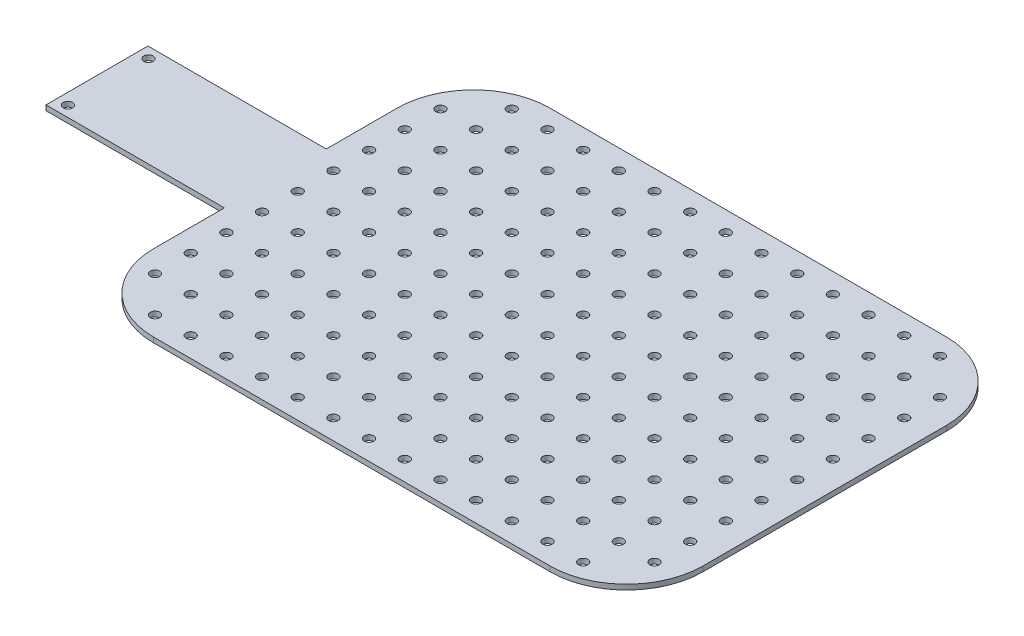
SolidWorks part; units mm, degrees
ref_plane "Front Plane" through (0, 0, 0) normal (0, 0, 1) x (1, 0, 0)
ref_plane "Top Plane" through (0, 0, 0) normal (0, 1, 0) x (1, 0, 0)
ref_plane "Right Plane" through (0, 0, 0) normal (1, 0, 0) x (0, 0, -1)
sketch "Sketch1" plane through (0, 0, 0) normal (0, 1, 0) x (1, 0, 0)
  line L0 (0, 0) -> (0, 155.575) construction
  line L1 (77.8, 155.575) -> (-77.8, 155.575)
  line L2 (-107.8, 125.575) -> (-107.8, 97.7875)
  line L3 (-107.8, 97.7875) -> (-177.8, 97.7875)
  line L4 (-177.8, 97.7875) -> (-177.8, 57.7875)
  line L5 (-177.8, 57.7875) -> (-107.8, 57.7875)
  line L6 (-107.8, 57.7875) -> (-107.8, 30)
  line L7 (-77.8, 0) -> (77.8, 0)
  line L8 (-173.4, 93.5875) -> (-173.4, 61.9875) construction
  line L9 (-177.8, 77.7875) -> (-107.8, 77.7875) construction
  line L10 (107.8, 97.7875) -> (107.8, 57.7875)
  line L11 (107.8, 57.7875) -> (107.8, 30)
  line L15 (107.8, 125.575) -> (107.8, 97.7875)
  circle A0 centre (-173.4, 93.5875) radius 1.85
  circle A1 centre (-173.4, 61.9875) radius 1.85
  arc A4 (107.8, 30) -> (77.8, 0) centre (77.8, 30) cw
  arc A5 (-107.8, 30) -> (-77.8, 0) centre (-77.8, 30) ccw
  arc A6 (107.8, 125.575) -> (77.8, 155.575) centre (77.8, 125.575) ccw
  arc A7 (-77.8, 155.575) -> (-107.8, 125.575) centre (-77.8, 125.575) ccw
  point P15 (-173.4, 77.7875)
  point P29 (107.8, 0)
  point P32 (-107.8, 0)
  point P35 (107.8, 155.575)
  point P38 (-107.8, 155.575)
  dimension "D5" = 3.7
  dimension "D8" = 30
  dimension "D1" = 155.575
  dimension "D2" = 177.8
  dimension "D3" = 40
  dimension "D4" = 31.6
  dimension "D6" = 4.4
  dimension "D7" = 70
extrude "Boss-Extrude1" add sketch "Sketch1" along normal blind 2
sketch "Sketch2" plane through (0, 2, 0) normal (0, 1, 0) x (1, 0, 0)
  line L0 (-99.0132, 8.7868) -> (-99.0132, 146.7882) construction
  line L1 (-99.0132, 146.7882) -> (99.0132, 146.7882) construction
  line L2 (99.0132, 146.7882) -> (99.0132, 8.7868) construction
  line L3 (99.0132, 8.7868) -> (-99.0132, 8.7868) construction
  line L4 (-177.8, 77.7875) -> (107.8, 77.7875) construction
  line L5 (-177.8, 97.7875) -> (-177.8, 57.7875) construction
  line L7 (107.8, 30) -> (107.8, 125.575) construction
  arc A0 (-107.8, 30) -> (-77.8, 0) centre (-77.8, 30) ccw construction
  arc A1 (-77.8, 155.575) -> (-107.8, 125.575) centre (-77.8, 125.575) ccw construction
  arc A2 (107.8, 125.575) -> (77.8, 155.575) centre (77.8, 125.575) ccw construction
  arc A3 (77.8, 0) -> (107.8, 30) centre (77.8, 30) ccw construction
  circle A4 centre (-99.0132, 21.7875) radius 1.85
  circle A5 centre (-99.0132, 35.7875) radius 1.85
  circle A6 centre (-99.0132, 49.7875) radius 1.85
  circle A7 centre (-99.0132, 63.7875) radius 1.85
  circle A8 centre (-99.0132, 77.7875) radius 1.85
  circle A9 centre (-99.0132, 91.7875) radius 1.85
  circle A10 centre (-99.0132, 105.7875) radius 1.85
  circle A11 centre (-99.0132, 119.7875) radius 1.85
  circle A12 centre (-99.0132, 133.7875) radius 1.85
  circle A13 centre (-85.0132, 63.7875) radius 1.85
  circle A14 centre (-85.0132, 49.7875) radius 1.85
  circle A15 centre (-85.0132, 35.7875) radius 1.85
  circle A16 centre (-85.0132, 21.7875) radius 1.85
  circle A17 centre (-85.0132, 91.7875) radius 1.85
  circle A18 centre (-85.0132, 105.7875) radius 1.85
  circle A19 centre (-85.0132, 77.7875) radius 1.85
  circle A20 centre (-85.0132, 133.7875) radius 1.85
  circle A21 centre (-85.0132, 119.7875) radius 1.85
  circle A22 centre (-71.0132, 63.7875) radius 1.85
  circle A23 centre (-71.0132, 49.7875) radius 1.85
  circle A24 centre (-71.0132, 35.7875) radius 1.85
  circle A25 centre (-71.0132, 21.7875) radius 1.85
  circle A26 centre (-71.0132, 91.7875) radius 1.85
  circle A27 centre (-71.0132, 105.7875) radius 1.85
  circle A28 centre (-71.0132, 77.7875) radius 1.85
  circle A29 centre (-71.0132, 133.7875) radius 1.85
  circle A30 centre (-71.0132, 119.7875) radius 1.85
  circle A31 centre (-57.0132, 63.7875) radius 1.85
  circle A32 centre (-57.0132, 49.7875) radius 1.85
  circle A33 centre (-57.0132, 35.7875) radius 1.85
  circle A34 centre (-57.0132, 21.7875) radius 1.85
  circle A35 centre (-57.0132, 91.7875) radius 1.85
  circle A36 centre (-57.0132, 105.7875) radius 1.85
  circle A37 centre (-57.0132, 77.7875) radius 1.85
  circle A38 centre (-57.0132, 133.7875) radius 1.85
  circle A39 centre (-57.0132, 119.7875) radius 1.85
  circle A40 centre (-43.0132, 63.7875) radius 1.85
  circle A41 centre (-43.0132, 49.7875) radius 1.85
  circle A42 centre (-43.0132, 35.7875) radius 1.85
  circle A43 centre (-43.0132, 21.7875) radius 1.85
  circle A44 centre (-43.0132, 91.7875) radius 1.85
  circle A45 centre (-43.0132, 105.7875) radius 1.85
  circle A46 centre (-43.0132, 77.7875) radius 1.85
  circle A47 centre (-43.0132, 133.7875) radius 1.85
  circle A48 centre (-43.0132, 119.7875) radius 1.85
  circle A49 centre (-29.0132, 63.7875) radius 1.85
  circle A50 centre (-29.0132, 49.7875) radius 1.85
  circle A51 centre (-29.0132, 35.7875) radius 1.85
  circle A52 centre (-29.0132, 21.7875) radius 1.85
  circle A53 centre (-29.0132, 91.7875) radius 1.85
  circle A54 centre (-29.0132, 105.7875) radius 1.85
  circle A55 centre (-29.0132, 77.7875) radius 1.85
  circle A56 centre (-29.0132, 133.7875) radius 1.85
  circle A57 centre (-29.0132, 119.7875) radius 1.85
  circle A58 centre (-15.0132, 63.7875) radius 1.85
  circle A59 centre (-15.0132, 49.7875) radius 1.85
  circle A60 centre (-15.0132, 35.7875) radius 1.85
  circle A61 centre (-15.0132, 21.7875) radius 1.85
  circle A62 centre (-15.0132, 91.7875) radius 1.85
  circle A63 centre (-15.0132, 105.7875) radius 1.85
  circle A64 centre (-15.0132, 77.7875) radius 1.85
  circle A65 centre (-15.0132, 133.7875) radius 1.85
  circle A66 centre (-15.0132, 119.7875) radius 1.85
  circle A67 centre (-1.0132, 63.7875) radius 1.85
  circle A68 centre (-1.0132, 49.7875) radius 1.85
  circle A69 centre (-1.0132, 35.7875) radius 1.85
  circle A70 centre (-1.0132, 21.7875) radius 1.85
  circle A71 centre (-1.0132, 91.7875) radius 1.85
  circle A72 centre (-1.0132, 105.7875) radius 1.85
  circle A73 centre (-1.0132, 77.7875) radius 1.85
  circle A74 centre (-1.0132, 133.7875) radius 1.85
  circle A75 centre (-1.0132, 119.7875) radius 1.85
  circle A76 centre (12.9868, 63.7875) radius 1.85
  circle A77 centre (12.9868, 49.7875) radius 1.85
  circle A78 centre (12.9868, 35.7875) radius 1.85
  circle A79 centre (12.9868, 21.7875) radius 1.85
  circle A80 centre (12.9868, 91.7875) radius 1.85
  circle A81 centre (12.9868, 105.7875) radius 1.85
  circle A82 centre (12.9868, 77.7875) radius 1.85
  circle A83 centre (12.9868, 133.7875) radius 1.85
  circle A84 centre (12.9868, 119.7875) radius 1.85
  circle A85 centre (26.9868, 63.7875) radius 1.85
  circle A86 centre (26.9868, 49.7875) radius 1.85
  circle A87 centre (26.9868, 35.7875) radius 1.85
  circle A88 centre (26.9868, 21.7875) radius 1.85
  circle A89 centre (26.9868, 91.7875) radius 1.85
  circle A90 centre (26.9868, 105.7875) radius 1.85
  circle A91 centre (26.9868, 77.7875) radius 1.85
  circle A92 centre (26.9868, 133.7875) radius 1.85
  circle A93 centre (26.9868, 119.7875) radius 1.85
  circle A94 centre (40.9868, 63.7875) radius 1.85
  circle A95 centre (40.9868, 49.7875) radius 1.85
  circle A96 centre (40.9868, 35.7875) radius 1.85
  circle A97 centre (40.9868, 21.7875) radius 1.85
  circle A98 centre (40.9868, 91.7875) radius 1.85
  circle A99 centre (40.9868, 105.7875) radius 1.85
  circle A100 centre (40.9868, 77.7875) radius 1.85
  circle A101 centre (40.9868, 133.7875) radius 1.85
  circle A102 centre (40.9868, 119.7875) radius 1.85
  circle A103 centre (54.9868, 63.7875) radius 1.85
  circle A104 centre (54.9868, 49.7875) radius 1.85
  circle A105 centre (54.9868, 35.7875) radius 1.85
  circle A106 centre (54.9868, 21.7875) radius 1.85
  circle A107 centre (54.9868, 91.7875) radius 1.85
  circle A108 centre (54.9868, 105.7875) radius 1.85
  circle A109 centre (54.9868, 77.7875) radius 1.85
  circle A110 centre (54.9868, 133.7875) radius 1.85
  circle A111 centre (54.9868, 119.7875) radius 1.85
  circle A112 centre (68.9868, 63.7875) radius 1.85
  circle A113 centre (68.9868, 49.7875) radius 1.85
  circle A114 centre (68.9868, 35.7875) radius 1.85
  circle A115 centre (68.9868, 21.7875) radius 1.85
  circle A116 centre (68.9868, 91.7875) radius 1.85
  circle A117 centre (68.9868, 105.7875) radius 1.85
  circle A118 centre (68.9868, 77.7875) radius 1.85
  circle A119 centre (68.9868, 133.7875) radius 1.85
  circle A120 centre (68.9868, 119.7875) radius 1.85
  circle A121 centre (82.9868, 63.7875) radius 1.85
  circle A122 centre (82.9868, 49.7875) radius 1.85
  circle A123 centre (82.9868, 35.7875) radius 1.85
  circle A124 centre (82.9868, 21.7875) radius 1.85
  circle A125 centre (82.9868, 91.7875) radius 1.85
  circle A126 centre (82.9868, 105.7875) radius 1.85
  circle A127 centre (82.9868, 77.7875) radius 1.85
  circle A128 centre (82.9868, 133.7875) radius 1.85
  circle A129 centre (82.9868, 119.7875) radius 1.85
  circle A130 centre (96.9868, 63.7875) radius 1.85
  circle A131 centre (96.9868, 49.7875) radius 1.85
  circle A132 centre (96.9868, 35.7875) radius 1.85
  circle A133 centre (96.9868, 21.7875) radius 1.85
  circle A134 centre (96.9868, 91.7875) radius 1.85
  circle A135 centre (96.9868, 105.7875) radius 1.85
  circle A136 centre (96.9868, 77.7875) radius 1.85
  circle A137 centre (96.9868, 133.7875) radius 1.85
  circle A138 centre (96.9868, 119.7875) radius 1.85
  circle A139 centre (-85.0132, 147.7875) radius 1.85
  circle A140 centre (-1.0132, 147.7875) radius 1.85
  circle A141 centre (-15.0132, 147.7875) radius 1.85
  circle A142 centre (-29.0132, 147.7875) radius 1.85
  circle A143 centre (-43.0132, 147.7875) radius 1.85
  circle A144 centre (-57.0132, 147.7875) radius 1.85
  circle A145 centre (-71.0132, 147.7875) radius 1.85
  circle A146 centre (12.9868, 147.7875) radius 1.85
  circle A147 centre (26.9868, 147.7875) radius 1.85
  circle A148 centre (82.9868, 147.7875) radius 1.85
  circle A149 centre (68.9868, 147.7875) radius 1.85
  circle A150 centre (54.9868, 147.7875) radius 1.85
  circle A151 centre (40.9868, 147.7875) radius 1.85
  circle A152 centre (-85.0132, 35.7875) radius 1.85
  circle A153 centre (-85.0132, 7.7875) radius 1.85
  circle A154 centre (-71.0132, 7.7875) radius 1.85
  circle A155 centre (-57.0132, 7.7875) radius 1.85
  circle A156 centre (-43.0132, 7.7875) radius 1.85
  circle A157 centre (-29.0132, 7.7875) radius 1.85
  circle A158 centre (-15.0132, 7.7875) radius 1.85
  circle A159 centre (-1.0132, 7.7875) radius 1.85
  circle A160 centre (12.9868, 7.7875) radius 1.85
  circle A161 centre (26.9868, 7.7875) radius 1.85
  circle A162 centre (40.9868, 7.7875) radius 1.85
  circle A163 centre (54.9868, 7.7875) radius 1.85
  circle A164 centre (68.9868, 7.7875) radius 1.85
  circle A165 centre (82.9868, 7.7875) radius 1.85
  dimension "D1" = 3.7
  dimension "D2" = 9
  dimension "D3" = 15
  dimension "D4" = 2
  dimension "D5" = 2
extrude "Cut-Extrude1" cut sketch "Sketch2" against normal blind 2
